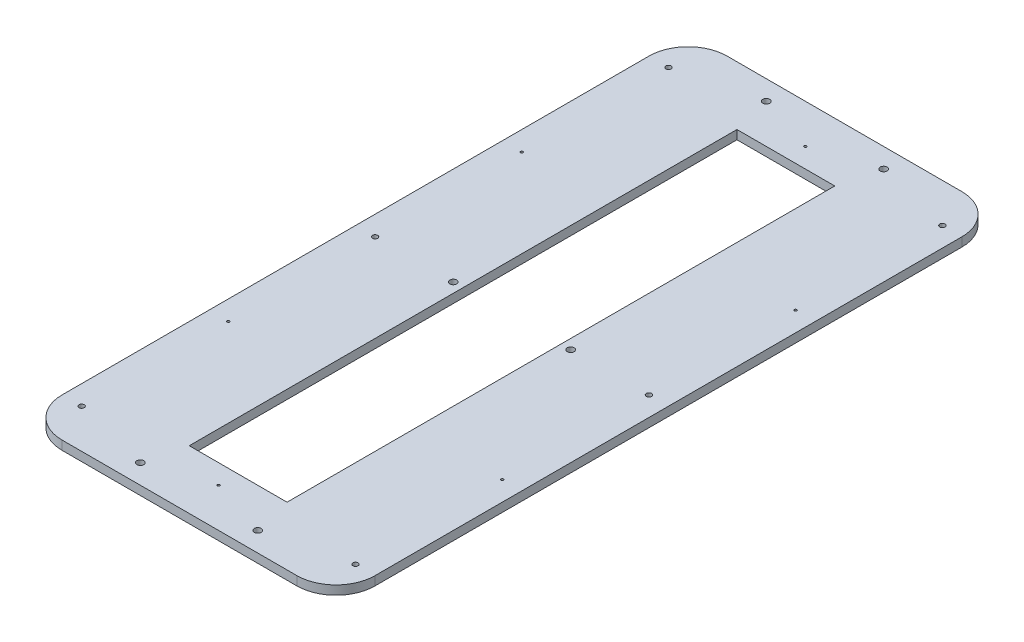
SolidWorks part; units mm, degrees
material "Acrylic (Medium-high impact)"
ref_plane "Front Plane" through (0, 0, 0) normal (0, 0, 1) x (1, 0, 0)
ref_plane "Top Plane" through (0, 0, 0) normal (0, 1, 0) x (1, 0, 0)
ref_plane "Right Plane" through (0, 0, 0) normal (1, 0, 0) x (0, 0, -1)
sketch "Sketch1" plane through (0, 0, 0) normal (0, 1, 0) x (1, 0, 0)
  line L1 (0, 0) -> (203.2, 0)
  line L2 (0, 0) -> (0, 431.8)
  line L3 (0, 431.8) -> (203.2, 431.8)
  line L4 (203.2, 0) -> (203.2, 431.8)
  dimension "D1" = 203.2
  dimension "D2" = 431.8
extrude "Boss-Extrude1" add sketch "Sketch1" along normal blind 5.8
hole_wizard "M4 Clearance Hole1" positions "Sketch6" profile "Sketch5" hole size "M4" standard "Ansi Metric"
sketch "Sketch6" plane through (0, 5.8, 0) normal (0, 1, 0) x (-1, 0, 0)
  line L4 (-101.6, 0) -> (-101.6, -431.8) construction
  line L8 (-63.5, -419.1) -> (-63.5, -12.7) construction
  line L10 (-139.7, -419.1) -> (-139.7, -12.7) construction
  line L15 (-63.5, -215.9) -> (-101.6, -215.9) construction
  line L16 (-101.6, -215.9) -> (-139.7, -215.9) construction
  line L19 (-203.2, -431.8) -> (0, -431.8) construction
  line L20 (-203.2, -431.8) -> (0, -431.8) construction
  line L21 (-63.5, -419.1) -> (-139.7, -419.1) construction
  line L24 (0, 0) -> (-203.2, 0) construction
  point P0 (-63.5, -419.1)
  point P1 (-139.7, -419.1)
  point P3 (-63.5, -215.9)
  point P5 (-139.7, -215.9)
  point P7 (-63.5, -12.7)
  point P9 (-139.7, -12.7)
  point P63 (-101.6, -431.8)
  dimension "D1" = 406.4
  dimension "D2" = 76.2
sketch "Sketch5" plane through (63.5, 5.8, -419.1) normal (1, 0, 0) x (0, 0, 1)
  line L0 (0, 0) -> (0, 14.0519)
  line L1 (0, 14.0519) -> (2.25, 12.7)
  line L2 (2.25, 12.7) -> (2.25, 0)
  line L5 (2.25, 0) -> (0, 0)
  line L10 (0, 14.0519) -> (-2.25, 12.7) construction
  line L11 (0, -6.35) -> (0, 107.95) construction
  dimension "Hole Dia." = 4.5
  dimension "Hole Depth" = 12.7
  dimension "Drill Angle" = 118
sketch "Sketch7" plane through (0, 5.8, 0) normal (0, 1, 0) x (1, 0, 0)
  line L0 (101.6, 38.1) -> (101.6, 0) construction
  line L1 (69.85, 393.7) -> (133.35, 393.7)
  line L2 (69.85, 393.7) -> (69.85, 38.1)
  line L3 (69.85, 38.1) -> (133.35, 38.1)
  line L4 (133.35, 393.7) -> (133.35, 38.1)
  line L5 (0, 0) -> (203.2, 0) construction
  line L6 (69.85, 215.9) -> (0, 215.9) construction
  line L8 (133.35, 215.9) -> (203.2, 215.9) construction
  line L10 (101.6, 393.7) -> (101.6, 431.8) construction
  line L11 (203.2, 431.8) -> (0, 431.8) construction
  line L12 (0, 431.8) -> (0, 0) construction
  line L13 (203.2, 0) -> (203.2, 431.8) construction
  dimension "D1" = 63.5
  dimension "D2" = 355.6
extrude "Cut-Extrude2" cut sketch "Sketch7" against normal through all
fillet "Fillet1" radius 25.4 4 edges at (203.2, 2.9, -431.8) (0, 2.9, -431.8) (203.2, 2.9, 0) (0, 2.9, 0)
hole_wizard "M3 Clearance Hole1" positions "Sketch9" profile "Sketch8" hole size "M3" standard "Ansi Metric"
sketch "Sketch9" plane through (0, 5.8, 0) normal (0, 1, 0) x (-1, 0, 0)
  line L0 (-190.5, -406.4) -> (-12.7, -406.4) construction
  line L1 (-12.7, -406.4) -> (-12.7, -25.4) construction
  line L2 (-12.7, -25.4) -> (-190.5, -25.4) construction
  line L3 (-190.5, -25.4) -> (-190.5, -406.4) construction
  line L5 (-101.6, -406.4) -> (-101.6, -431.8) construction
  line L6 (-177.8, -431.8) -> (-25.4, -431.8) construction
  line L8 (-101.6, -25.4) -> (-101.6, 0) construction
  line L9 (-25.4, 0) -> (-177.8, 0) construction
  point P0 (-190.5, -406.4)
  point P1 (-190.5, -25.4)
  point P3 (-12.7, -25.4)
  point P5 (-12.7, -406.4)
  point P27 (-190.5, -215.9)
  point P29 (-12.7, -215.9)
  dimension "D1" = 381
  dimension "D2" = 177.8
sketch "Sketch8" plane through (190.5, 5.8, -406.4) normal (1, 0, 0) x (0, 0, 1)
  line L0 (0, 0) -> (0, 13.7215)
  line L1 (0, 13.7215) -> (1.7, 12.7)
  line L2 (1.7, 12.7) -> (1.7, 0)
  line L5 (1.7, 0) -> (0, 0)
  line L10 (0, 13.7215) -> (-1.7, 12.7) construction
  line L11 (0, -6.35) -> (0, 107.95) construction
  dimension "Hole Dia." = 3.4
  dimension "Hole Depth" = 12.7
  dimension "Drill Angle" = 118
sketch "Sketch10" plane through (0, 5.8, 0) normal (0, 1, 0) x (-1, 0, 0)
  line L0 (-190.5, -25.4) -> (-12.7, -25.4) construction
  line L1 (-12.7, -25.4) -> (-12.7, -215.9) construction
  line L2 (-190.5, -25.4) -> (-190.5, -215.9) construction
  line L3 (-190.5, -215.9) -> (-12.7, -215.9) construction
  circle A0 centre (-190.5, -120.65) radius 0.7938
  circle A1 centre (-12.7, -120.65) radius 0.7937
  circle A2 centre (-101.6, -25.4) radius 0.7937
  circle A3 centre (-101.6, -406.4) radius 0.7938
  circle A4 centre (-12.7, -311.15) radius 0.7938
  circle A5 centre (-190.5, -311.15) radius 0.7938
  dimension "D1" = 1.5875
extrude "Cut-Extrude3" cut sketch "Sketch10" against normal through all
